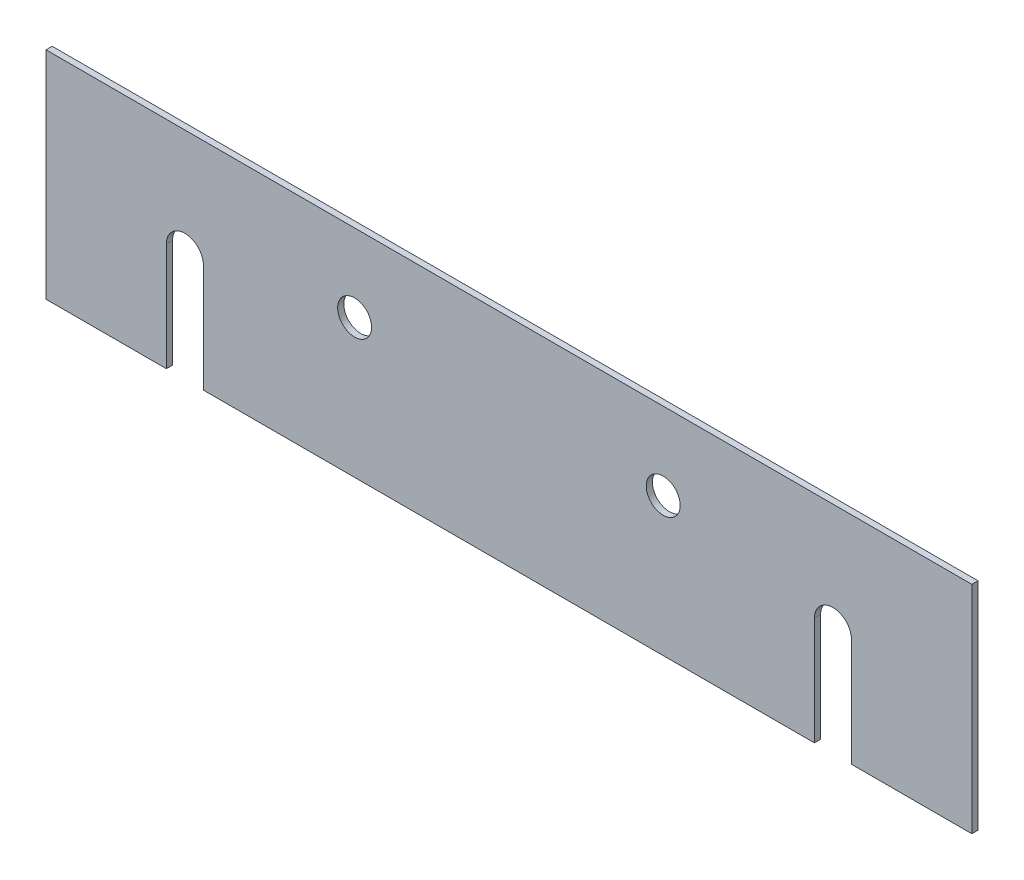
SolidWorks part; units mm, degrees
material "Galvanized Steel"
ref_plane "Front Plane" through (0, 0, 0) normal (0, 0, 1) x (1, 0, 0)
ref_plane "Top Plane" through (0, 0, 0) normal (0, 1, 0) x (1, 0, 0)
ref_plane "Right Plane" through (0, 0, 0) normal (1, 0, 0) x (0, 0, -1)
sketch "Sketch1" plane through (0, 0, 0) normal (0, 0, 1) x (1, 0, 0)
  line L1 (103.18, 46.4198) -> (-196.82, 46.4198)
  line L2 (103.18, 46.4198) -> (103.18, -23.5802)
  line L3 (103.18, -23.5802) -> (64.18, -23.5802)
  line L4 (-196.82, 46.4198) -> (-196.82, -23.5802)
  line L5 (52.18, -23.5802) -> (52.18, 11.4198)
  line L6 (64.18, -23.5802) -> (64.18, 11.4198)
  line L7 (52.18, -23.5802) -> (-145.82, -23.5802)
  line L8 (-157.82, -23.5802) -> (-157.82, 11.4198)
  line L9 (-145.82, -23.5802) -> (-145.82, 11.4198)
  line L10 (-157.82, -23.5802) -> (-196.82, -23.5802)
  arc A1 (64.18, 11.4198) -> (52.18, 11.4198) centre (58.18, 11.4198) ccw
  arc A3 (-145.82, 11.4198) -> (-157.82, 11.4198) centre (-151.82, 11.4198) ccw
  circle A4 centre (-96.82, 21.2963) radius 5.5
  circle A5 centre (3.18, 21.2963) radius 5.5
  point P6 (58.18, -14.5062)
  point P11 (-151.82, -18.8272)
  dimension "D3" = 35
  dimension "D11" = 11
  dimension "D12" = 11
  dimension "D1" = 300
  dimension "D2" = 70
  dimension "D4" = 12
  dimension "D5" = 45
  dimension "D6" = 45
  dimension "D7" = 12
  dimension "D8" = 35
  dimension "D9" = 100
  dimension "D10" = 100
extrude "Boss-Extrude1" add sketch "Sketch1" along normal blind 2
